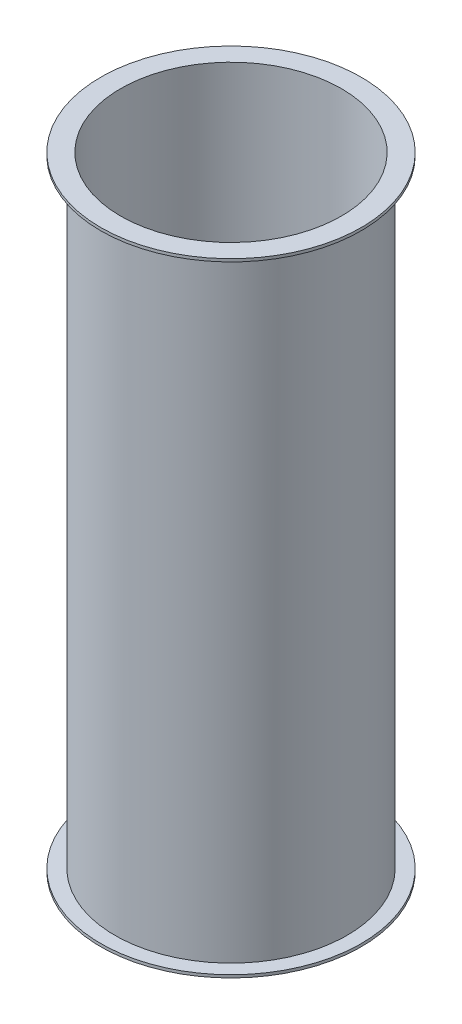
SolidWorks part; units mm, degrees
material "AISI 304"
ref_plane "Piano frontale" through (0, 0, 0) normal (0, 0, 1) x (1, 0, 0)
ref_plane "Piano superiore" through (0, 0, 0) normal (0, 1, 0) x (1, 0, 0)
ref_plane "Piano destro" through (0, 0, 0) normal (1, 0, 0) x (0, 0, -1)
sketch "Schizzo1" plane through (0, 0, 0) normal (0, 1, 0) x (1, 0, 0)
  circle A0 centre (0, 0) radius 39
extrude "Estrusione-Sottile1" add sketch "Schizzo1" along normal mid plane 220 thin
sketch "Schizzo2" plane through (0, 110, 0) normal (0, 1, 0) x (1, 0, 0)
  circle A0 centre (0, 0) radius 41 construction
  circle A1 centre (0, 0) radius 41
  circle A2 centre (0, 0) radius 46
extrude "Estrusione-Estrusione1" add sketch "Schizzo2" against normal blind 1
sketch "Schizzo3" plane through (0, -110, 0) normal (0, -1, 0) x (1, 0, 0)
  circle A0 centre (0, 0) radius 41 construction
  circle A1 centre (0, 0) radius 41
  circle A2 centre (0, 0) radius 46 construction
  circle A3 centre (0, 0) radius 46
extrude "Estrusione-Estrusione2" add sketch "Schizzo3" against normal blind 1
sketch "Schizzo4" plane through (0, -110, 0) normal (0, -1, 0) x (1, 0, 0)
  line L0 (24.5909, 0) -> (-24.5909, 0) construction
  line L1 (0, -22.0959) -> (0, 22.0959) construction
  point P5 (0, 0)
  point P9 (0, 0)
sketch "Schizzo5" plane through (0, 110, 0) normal (0, 1, 0) x (1, 0, 0)
  line L0 (24.5909, 0) -> (-24.5909, 0) construction
  line L1 (24.5909, 0) -> (-24.5909, 0) construction
  line L2 (0, 22.0959) -> (0, -22.0959) construction
  line L3 (0, 22.0959) -> (0, -22.0959) construction
